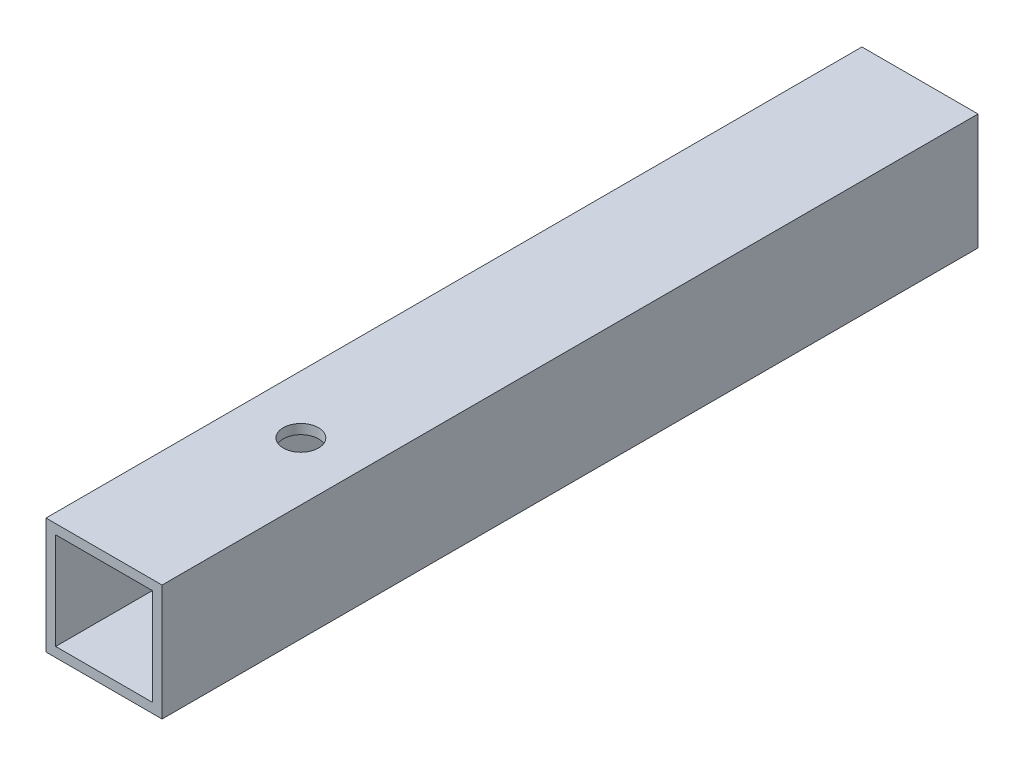
SolidWorks part; units mm, degrees
ref_plane "Front Plane" through (0, 0, 0) normal (0, 0, 1) x (1, 0, 0)
ref_plane "Top Plane" through (0, 0, 0) normal (0, 1, 0) x (1, 0, 0)
ref_plane "Right Plane" through (0, 0, 0) normal (1, 0, 0) x (0, 0, -1)
sketch "Sketch1" plane through (0, 0, 0) normal (0, 0, 1) x (0, -1, 0)
  line L1 (-9.525, 9.525) -> (9.525, 9.525)
  line L2 (-9.525, 9.525) -> (-9.525, -9.525)
  line L3 (-9.525, -9.525) -> (9.525, -9.525)
  line L4 (9.525, 9.525) -> (9.525, -9.525)
  line L5 (-9.525, 9.525) -> (9.525, -9.525) construction
  line L6 (-9.525, -9.525) -> (9.525, 9.525) construction
  line L7 (-7.9375, 7.9375) -> (7.9375, 7.9375)
  line L8 (-7.9375, 7.9375) -> (-7.9375, -7.9375)
  line L9 (-7.9375, -7.9375) -> (7.9375, -7.9375)
  line L10 (7.9375, 7.9375) -> (7.9375, -7.9375)
  line L11 (-7.9375, 7.9375) -> (7.9375, -7.9375) construction
  line L12 (-7.9375, -7.9375) -> (7.9375, 7.9375) construction
  point P0 (0, 0)
  point P5 (0, 0)
  dimension "D1" = 15.875
  dimension "D2" = 19.05
extrude "Boss-Extrude1" add sketch "Sketch1" along normal mid plane 133.9032
sketch "Sketch2" plane through (0, 9.525, 0) normal (0, 1, 0) x (1, 0, 0)
  line L0 (0, -66.9516) -> (0, -34.6484) construction
  line L1 (9.525, -66.9516) -> (-9.525, -66.9516) construction
  line L2 (9.525, 66.9516) -> (-9.525, 66.9516) construction
  circle A0 centre (0, -34.6484) radius 2.8956
  point P8 (0, 66.9516)
  dimension "D2" = 5.7912
  dimension "D1" = 101.6
extrude "BasePlateMountHole" cut sketch "Sketch2" against normal through all
equation "\"Height\"= 32in"
equation "\"Width\"= 23in"
equation "\"Depth\"= 20in"
equation "\"Plexi\"= .121in"
equation "\"MagnetThickness\"=3mm"
equation "\"MagnetDiameter\"=12mm"
equation "\"DoorPlexi\" = \"Plexi\""
equation "\"BasePlateThickness\" = 0.5in"
equation "\"BasePlateWidth\" = \"Width\"+\"EBWidth\"-2*\"Plexi\""
equation "\"BasePlateDepth\" = \"Depth\"-\"Plexi\"-\"DoorPlexi\""
equation "\"Boxsize\" = .75in"
equation "\"Boxinner\" = .625in"
equation "\"CornerCube\" = 0.75in"
equation "\"FingerLength\" = 1.125in"
equation "\"FingerWidth\" = .625in"
equation "\"Cutwidth\"= .016in"
equation "\"Earsize\"= 1in + \"Cutwidth\" /2"
equation "\"Slotsize\" = 1in - \"CutWidth\" / 2"
equation "\"InnerWidth\" = \"Width\" - 2* \"Plexi\""
equation "\"InnerHeight\" = \"Height\" -2 * \"Plexi\""
equation "\"InnerDepth\" = \"Depth\" - 2*\"Plexi\""
equation "\"RearNumHoles\" = 7"
equation "\"RearHolesBorder\" = 2.2"
equation "\"RearHoleSpacing\" = (\"Width\" - 2*\"RearHolesBorder\") / (\"RearNumHoles\"-1)"
equation "\"RearBarLength\" = (\"InnerWidth\"-2*\"CornerCube\")"
equation "\"RearTopNumHoles\" = 6"
equation "\"RearTopHolesBorder\" = 2.5"
equation "\"RearTopHolesSpacing\" = (\"Width\" - 2*\"RearTopHolesBorder\") / (\"RearTopNumHoles\"-1)"
equation "\"SideTopNumHoles\" = 5"
equation "\"SideTopHoleOffset\"=\"CornerCube\"+\"FingerLength\"+\"Plexi\"+.5"
equation "\"SideHorizNumHoles\" = 6"
equation "\"SideHorizHoleBorder\" = 2.25"
equation "\"SideVertBarLength\"=\"Height\"-\"BasePlateThickness\"-2*\"CornerCube\"-\"Plexi\""
equation "\"SideVertNumHoles\" = 6"
equation "\"SideVertHolesBorder\" = \"CornerCube\"+\"FingerLength\"+.9"
equation "\"SideVertHoleSpacing\" = (\"InnerHeight\" - 2*\"SideVertHolesBorder\") / (\"SideVertNumHoles\"-1)"
equation "\"RearSideVertNumHoles\" = 7"
equation "\"RearSideVertHolesBorder\" = 2.5"
equation "\"RearSideVertHoleSpacing\" = (\"InnerHeight\" - 2*\"RearSideVertHolesBorder\") / (\"RearSideVertNumHoles\"-1)"
equation "\"RivetDia\" = .228in"
equation "\"SlotDepth\" = \"Plexi\" + 0.75in + .005in"
equation "\"SideSlotWidth\"   = \"Plexi\"+.005in"
equation "\"SidePanelVertSpacing\" = (\"Height\"-2*(1.75-\"Plexi\")) / 5"
equation "\"BottomPanelSideHoleSpacing\" = (\"InnerDepth\"-2*(1.75-\"Plexi\")) / 4"
equation "\"FrontDoorGap\" = .1in"
equation "\"TopDepth\" = \"Depth\"-\"DoorPlexi\"-\"FrontDoorGap\""
equation "\"TopBarDepth\" = \"Depth\"-\"DoorPlexi\"-\"Plexi\"-2*\"MagnetThickness\"-2*\"CornerCube\""
equation "\"CoolerDepth\" = 12in"
equation "\"D1@Boss-Extrude1\"=\"ShelfBarDepth\""
equation "\"SideTopHoleSpacing\" = (\"TopBarDepth\"-2*\"SideTopHoleOffset\") / (\"SideTopNumHoles\"-1)"
equation "\"SideHorizHoleSpacing\" = (\"TopBarDepth\"-2*\"SideHorizHoleBorder\") / (\"SideHorizNumHoles\"-1)"
equation "\"ShelfDepth\" = \"TopBarDepth\"+\"CornerCube\"-\"CoolerDepth\""
equation "\"BoxsizeHalf\" = \"Boxsize\"/2"
equation "\"ShelfBarDepth\"=\"ShelfDepth\"-2*\"CornerCube\""
equation "\"ShelfWidth\" = \"EBWidth\"-\"ShelfGap\""
equation "\"ShelfBarWidth\" = \"EBWidth\"-\"Boxsize\""
equation "\"ShelfGap\" = 0.5in"
equation "\"ShelfBarWidthShort\" = \"ShelfBarWidth\"-\"Boxsize\"-\"ShelfGap\""
equation "\"IntakeWidth\"=4in"
equation "\"IntakeHeight\"=2in"
equation "\"ExhaustWidth\"=4in"
equation "\"ExhaustHeight\"=2in"
equation "\"VentSpacing\"=7in"
equation "\"AngleBracketLength\"=20mm"
equation "\"AngleBracketWidth\"=10mm"
equation "\"AngleBracketThickness\"=1.5mm"
equation "\"AngleBracketHolePos\"=15mm"
equation "\"AngleBracketHoleDia\"=\"RivetDia\""
equation "\"ShelfBarAngleHole\"=\"ShelfGap\"+\"Boxsize\"+\"AngleBracketHolePos\""
equation "\"EBWidth\" = 9in"
equation "\"ComponentMountDia\"=0.1770"
equation "\"ShelfThickness\" = .220in"
equation "\"BinderPostDia\" = .228in"
equation "\"ShelfHeight1\" = 13in"
equation "\"ShelfHeight2\" = 24in"
equation "\"VentVertLocation\"=12.75in"
equation "\"PSBracketThickness\" = .0641in"
equation "\"D2@Sketch2\"=\"BinderPostDia\""
equation "\"EBForwardMountOffset\" = 4.0in"
equation "\"EBForwardMount\" = 2*\"Boxsize\"+\"CoolerDepth\"+\"EBForwardMountOffset\""
equation "\"D1@Sketch2\"=\"EBForwardMountOffset\""
